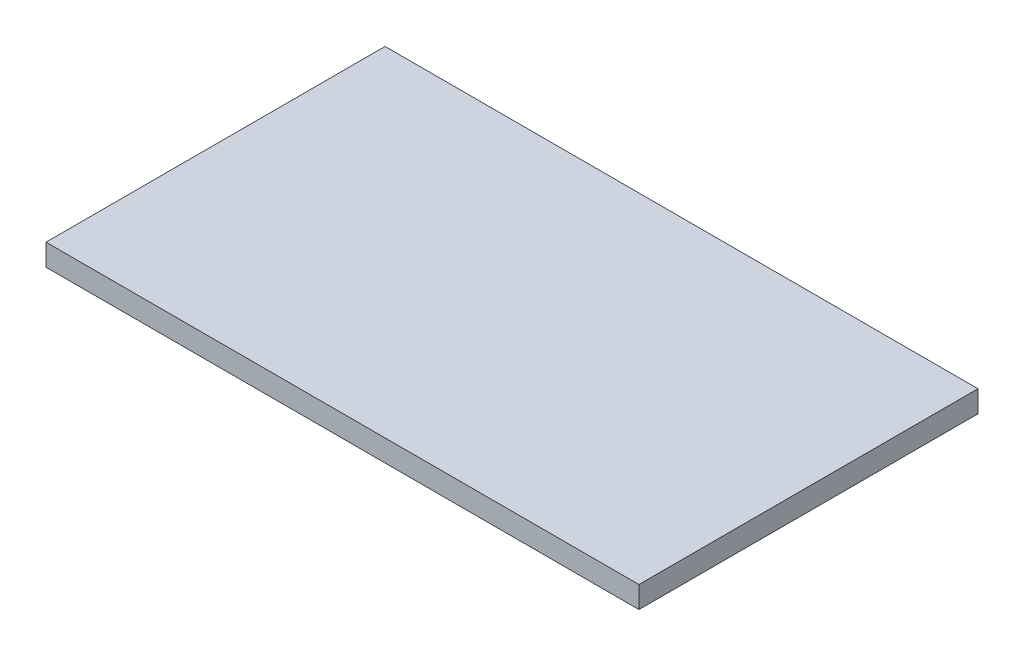
SolidWorks part; units mm, degrees
material "柚木"
ref_plane "前视基准面" through (0, 0, 0) normal (0, 0, 1) x (1, 0, 0)
ref_plane "上视基准面" through (0, 0, 0) normal (0, 1, 0) x (1, 0, 0)
ref_plane "右视基准面" through (0, 0, 0) normal (1, 0, 0) x (0, 0, -1)
sketch "草图1" plane through (0, 0, 0) normal (0, 1, 0) x (1, 0, 0)
  line L1 (-45.9995, 12.4486) -> (25.0005, 12.4486)
  line L2 (-45.9995, 12.4486) -> (-45.9995, -28.1514)
  line L3 (-45.9995, -28.1514) -> (25.0005, -28.1514)
  line L4 (25.0005, 12.4486) -> (25.0005, -28.1514)
  dimension "D1" = 71
  dimension "D2" = 40.6
extrude "凸台-拉伸1" add sketch "草图1" along normal blind 2.6
